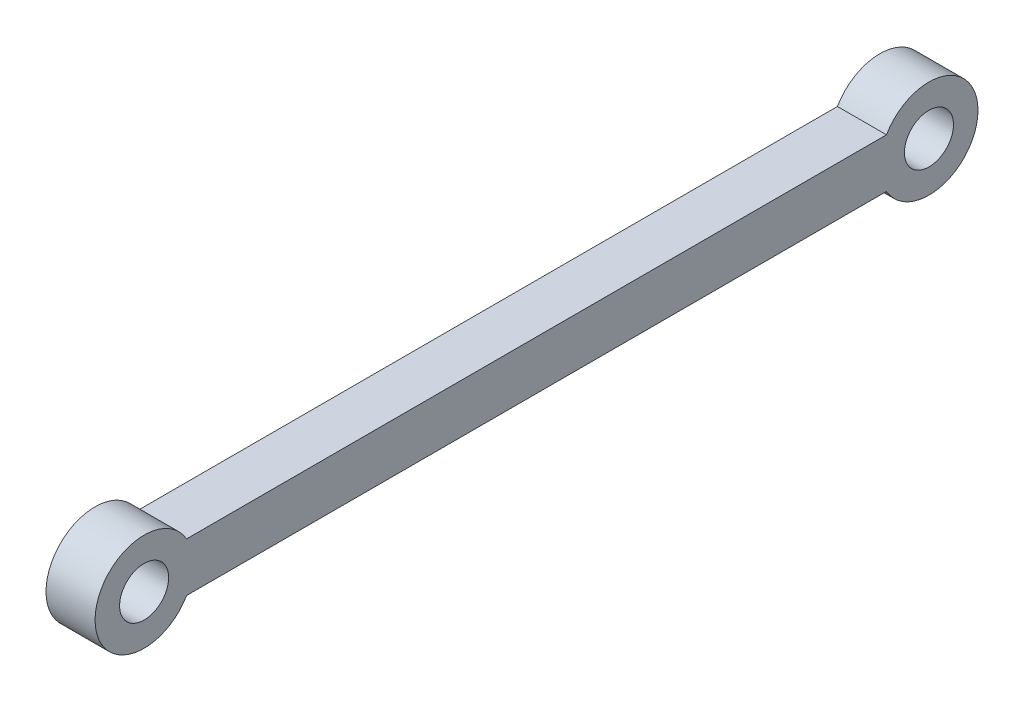
SolidWorks part; units mm, degrees
ref_plane "정면" through (0, 0, 0) normal (0, 0, 1) x (1, 0, 0)
ref_plane "윗면" through (0, 0, 0) normal (0, 1, 0) x (1, 0, 0)
ref_plane "우측면" through (0, 0, 0) normal (1, 0, 0) x (0, 0, -1)
sketch "스케치1" plane through (0, 0, 0) normal (1, 0, 0) x (0, 0, -1)
  line L0 (-20, 0) -> (20, 0) construction
  line L1 (-17.8349, 1.25) -> (17.8349, 1.25)
  line L3 (-17.8349, -1.25) -> (17.8349, -1.25)
  line L5 (0, 1.25) -> (0, -1.25) construction
  arc A0 (-17.8349, 1.25) -> (-17.8349, -1.25) centre (-20, 0) ccw
  circle A1 centre (-20, 0) radius 1.25
  arc A2 (17.8349, -1.25) -> (17.8349, 1.25) centre (20, 0) ccw
  circle A3 centre (20, 0) radius 1.25
  dimension "D3" = 5
  dimension "D4" = 5
  dimension "D1" = 2.5
  dimension "D2" = 40
extrude "보스-돌출1" add sketch "스케치1" along normal blind 2.5
equation "\"link11\" = 80"
equation "\"link12\" = 40"
equation "\"link21\"= 60"
equation "\"link22\"= 40"
equation "\"link31\"= 50"
equation "\"link32\"= 40"
equation "\"link41\"= 40"
equation "\"link42\"= 40"
equation "\"D2@스케치1\"=\"link32\""
